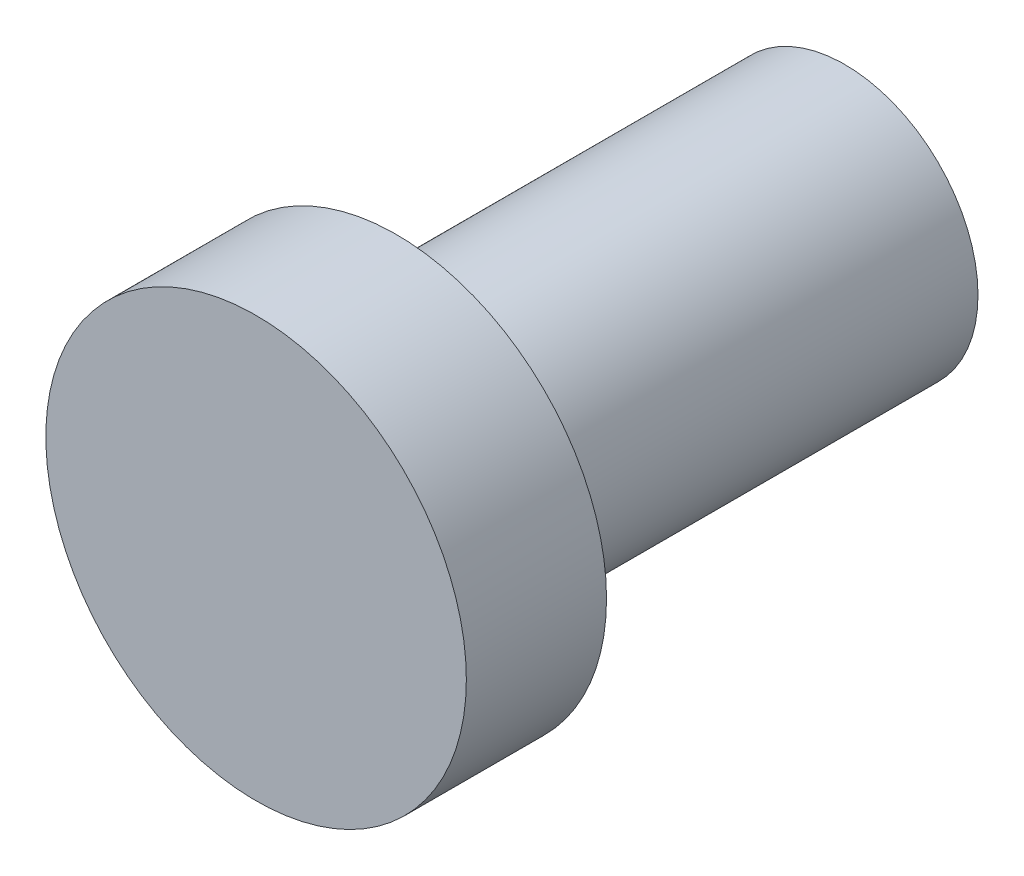
SolidWorks part; units mm, degrees
ref_plane "Front Plane" through (0, 0, 0) normal (0, 0, 1) x (1, 0, 0)
ref_plane "Top Plane" through (0, 0, 0) normal (0, 1, 0) x (1, 0, 0)
ref_plane "Right Plane" through (0, 0, 0) normal (1, 0, 0) x (0, 0, -1)
sketch "Sketch1" plane through (0, 0, 0) normal (0, 0, 1) x (1, 0, 0)
  circle A0 centre (0, 0) radius 4.75
  dimension "D1" = 9.5
extrude "Boss-Extrude1" add sketch "Sketch1" along normal blind 16
sketch "Sketch2" plane through (0, 0, 16) normal (0, 0, 1) x (1, 0, 0)
  circle A0 centre (0, 0) radius 7.5
  dimension "D1" = 15
extrude "Boss-Extrude2" add sketch "Sketch2" along normal blind 5
sketch "Sketch3" plane through (0, 0, 0) normal (0, 0, -1) x (-1, 0, 0)
  circle A0 centre (0, 0) radius 3.5
  dimension "D1" = 7
extrude "Cut-Extrude1" cut sketch "Sketch3" against normal blind 12 draft 6
